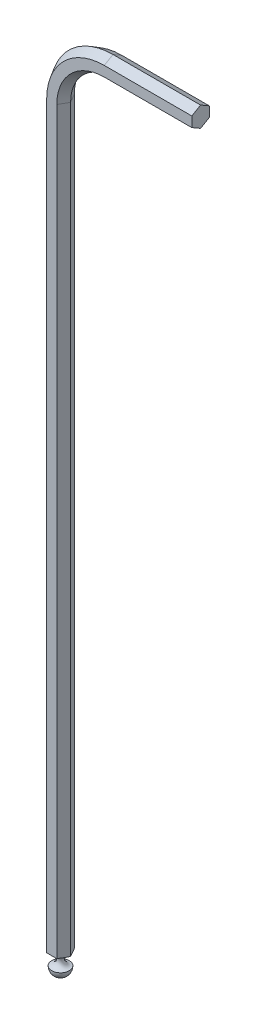
SolidWorks part; units mm, degrees
ref_plane "Vorne" through (0, 0, 0) normal (0, 0, 1) x (1, 0, 0)
ref_plane "Oben" through (0, 0, 0) normal (0, 1, 0) x (1, 0, 0)
ref_plane "Rechts" through (0, 0, 0) normal (1, 0, 0) x (0, 0, -1)
sketch "Skizze1" plane through (0, 0, 0) normal (0, 0, 1) x (1, 0, 0)
  line L0 (0, 0) -> (0, 86)
  line L1 (6, 92) -> (16, 92)
  arc A0 (0, 86) -> (6, 92) centre (6, 86) cw
  point P6 (0, 92)
  dimension "D3" = 6
  dimension "D1" = 92
  dimension "D2" = 16
sketch "Skizze3" plane through (0, 0, 0) normal (0, 1, 0) x (1, 0, 0)
  line L0 (-1.1547, 0) -> (1.1547, 0) construction
  line L1 (-0.5774, 1) -> (-1.1547, 0)
  line L2 (-1.1547, 0) -> (-0.5774, -1)
  line L3 (-0.5774, -1) -> (0.5774, -1)
  line L4 (0.5774, -1) -> (1.1547, 0)
  line L5 (1.1547, 0) -> (0.5774, 1)
  line L6 (0.5774, 1) -> (-0.5774, 1)
  circle A0 centre (0, 0) radius 1 construction
  dimension "D1" = 2
sweep "Austragung4" add profiles "Skizze3" path "Skizze1"
sketch "Skizze6" plane through (0, 0, 0) normal (1, 0, 0) x (0, 0, -1)
  line L0 (0, 7.8104) -> (0, -7.0578) construction
  line L1 (-1, 86) -> (-1, 0) construction
  line L2 (0, -1) -> (0, 1)
  line L3 (1, 86) -> (1, 0) construction
  arc A0 (0, -1) -> (0, 1) centre (0, 0) ccw
revolve "Rotation5" add sketch "Skizze6" angle 360 about L0
sketch "Skizze8" plane through (0, 0, 0) normal (0, 0, 1) x (1, 0, 0)
  line L0 (0, 0) -> (0, 50.305) construction
  line L1 (-3.0586, -0.2536) -> (-1.1547, 0)
  line L2 (-1.1547, 86) -> (-1.1547, 0) construction
  line L3 (-3.0586, 0.7464) -> (1.1547, 0.7464) construction
  line L4 (-1.1547, 0) -> (-0.9759, 1.4691) construction
  line L5 (-0.9759, 1.4691) -> (-3.0586, 1.7464)
  line L6 (-3.0586, 1.7464) -> (-3.0586, -0.2536)
  line L7 (1.1547, 86) -> (1.1547, 0) construction
  arc A0 (-1.1547, 0) -> (-0.9759, 1.4691) centre (-1.0736, 0.7355) ccw
  point P14 (4.4502, 0.7464)
  dimension "D1" = 2
  dimension "D4" = 0.74
  dimension "D2" = 1.9039
  dimension "D3" = 6.94
revolve "Schnitt-Rotation1" cut sketch "Skizze8" angle 360 about L0
